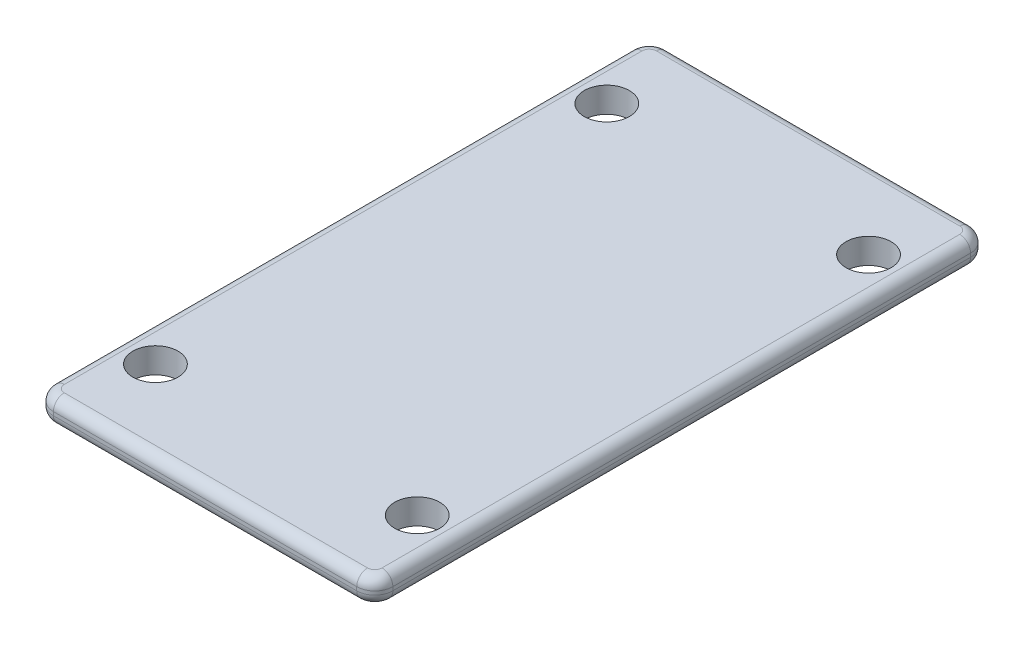
SolidWorks part; units mm, degrees
ref_plane "Front Plane" through (0, 0, 0) normal (0, 0, 1) x (1, 0, 0)
ref_plane "Top Plane" through (0, 0, 0) normal (0, 1, 0) x (1, 0, 0)
ref_plane "Right Plane" through (0, 0, 0) normal (1, 0, 0) x (0, 0, -1)
sketch "Sketch1" plane through (0, 0, 0) normal (0, 1, 0) x (1, 0, 0)
  line L0 (-9.4, 0) -> (9.4, 0) construction
  line L1 (9.4, -17) -> (-9.4, -17)
  line L2 (9.4, -17) -> (9.4, 17)
  line L3 (9.4, 17) -> (-9.4, 17)
  line L4 (-9.4, -17) -> (-9.4, 17)
  line L5 (9.4, -17) -> (-9.4, 17) construction
  line L6 (9.4, 17) -> (-9.4, -17) construction
  line L7 (0, -17) -> (0, 17) construction
  circle A0 centre (-7.25, 12.5) radius 1.25
  circle A1 centre (7.25, 12.5) radius 1.25
  circle A2 centre (-7.25, -12.5) radius 1.25
  circle A3 centre (7.25, -12.5) radius 1.25
  point P0 (0, 0)
  dimension "D5" = 2.5
  dimension "D1" = 18.8
  dimension "D2" = 34
  dimension "D3" = 25
  dimension "D4" = 14.5
extrude "Cable Plate Extrude" add sketch "Sketch1" along normal blind 1.4
fillet "Fillet2" radius 1 4 edges at (-9.4, 0.7, 17) (9.4, 0.7, 17) (9.4, 0.7, -17) (-9.4, 0.7, -17)
fillet "Fillet1" radius 0.6 16 edges at (0, 0, 17) (0, 1.4, 17) (9.4, 0, 0) (9.4, 1.4, 0) (0, 0, -17) (-9.4, 0, 0) (0, 1.4, -17) (-9.4, 1.4, 0) (-9.1071, 0, -16.7071) (9.1071, 0, -16.7071) (9.1071, 0, 16.7071) (-9.1071, 0, 16.7071) (-9.1071, 1.4, -16.7071) (9.1071, 1.4, -16.7071) (9.1071, 1.4, 16.7071) (-9.1071, 1.4, 16.7071)
equation "\"PLA_shrink\"=0.3mm"
equation "\"fit_sliding\"=0.5mm"
equation "\"fit_snap\"=0.3mm"
equation "\"fit_tight\"=0.2mm"
equation "\"m2_tap\"= 1.75mm + \"PLA_shrink\""
equation "\"m2_thin_wall\"= 1.9mm + \"PLA_shrink\""
equation "\"m2_standard\"= 2.2mm + \"PLA_shrink\""
equation "\"m2_head\"= 3.45mm + \"PLA_shrink\""
equation "\"m2.5_tap\"= 2.05 + \"PLA_shrink\""
equation "\"m2.5_standard\"= 2.75 + \"PLA_shrink\""
equation "\"m2.5_head\"= 5mm + \"PLA_shrink\""
equation "\"m3_tap\"= 2.5mm + \"PLA_shrink\""
equation "\"m3_standard\"= 3.3mm + \"PLA_shrink\""
equation "\"m3_head\"= 6mm + \"PLA_shrink\""
equation "\"connector_width\"= 9.35mm"
equation "\"wire_width\"= 3.1mm + \"PLA_shrink\""
equation "\"D5@Sketch1\"=\"m2_standard\""
